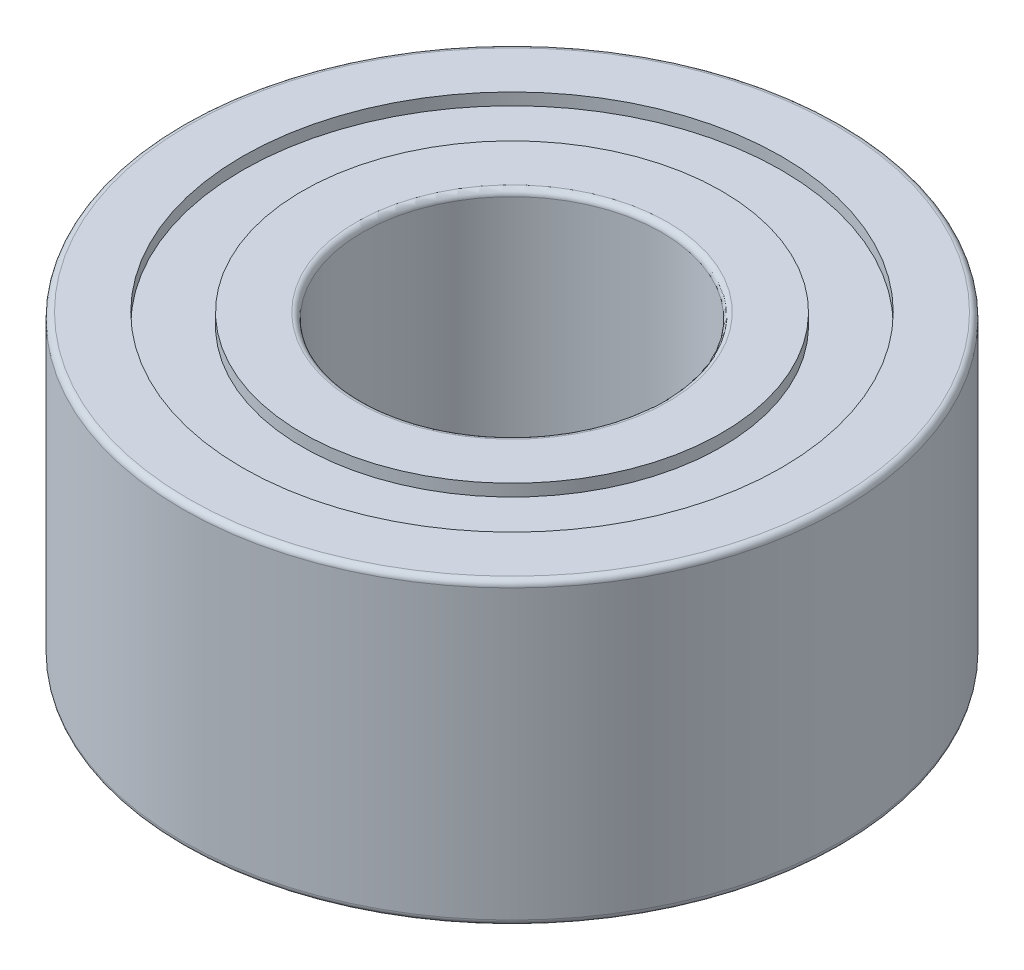
SolidWorks part; units mm, degrees
ref_plane "Alzado" through (0, 0, 0) normal (0, 0, 1) x (1, 0, 0)
ref_plane "Planta" through (0, 0, 0) normal (0, 1, 0) x (1, 0, 0)
ref_plane "Vista lateral" through (0, 0, 0) normal (1, 0, 0) x (0, 0, -1)
sketch "Croquis1" plane through (0, 0, 0) normal (1, 0, 0) x (0, 0, -1)
  line L0 (0, -2.2552) -> (0, 2.2552) construction
  line L1 (2.5, -2.4) -> (2.5, 2.4)
  line L2 (2.6, 2.5) -> (3.5, 2.5)
  line L3 (3.5, 2.5) -> (3.5, 2.3)
  line L4 (3.5, 2.3) -> (4.5, 2.3)
  line L5 (4.5, 2.3) -> (4.5, 2.5)
  line L6 (4.5, 2.5) -> (5.4, 2.5)
  line L7 (5.5, 2.4) -> (5.5, -2.4)
  line L8 (5.4, -2.5) -> (4.7796, -2.5)
  line L9 (4.7796, -2.5) -> (4.7796, -2.3)
  line L10 (4.7796, -2.3) -> (3.2204, -2.3)
  line L11 (3.2204, -2.3) -> (3.2204, -2.5)
  line L12 (3.2204, -2.5) -> (2.6, -2.5)
  arc A0 (2.5, 2.4) -> (2.6, 2.5) centre (2.6, 2.4) cw
  arc A1 (2.5, -2.4) -> (2.6, -2.5) centre (2.6, -2.4) ccw
  arc A2 (5.5, -2.4) -> (5.4, -2.5) centre (5.4, -2.4) cw
  arc A3 (5.4, 2.5) -> (5.5, 2.4) centre (5.4, 2.4) cw
  point P0 (0, 0)
  point P4 (0, 0)
  point P8 (2.5, 0)
  point P25 (5.5, -2.5)
  point P28 (5.5, 2.5)
  dimension "D5" = 0.1
  dimension "D1" = 2.5
  dimension "D2" = 5.5
  dimension "D3" = 5
  dimension "D4" = 0.2
  dimension "D6" = 1
revolve "Revolución1" add sketch "Croquis1" angle 360 about L0
